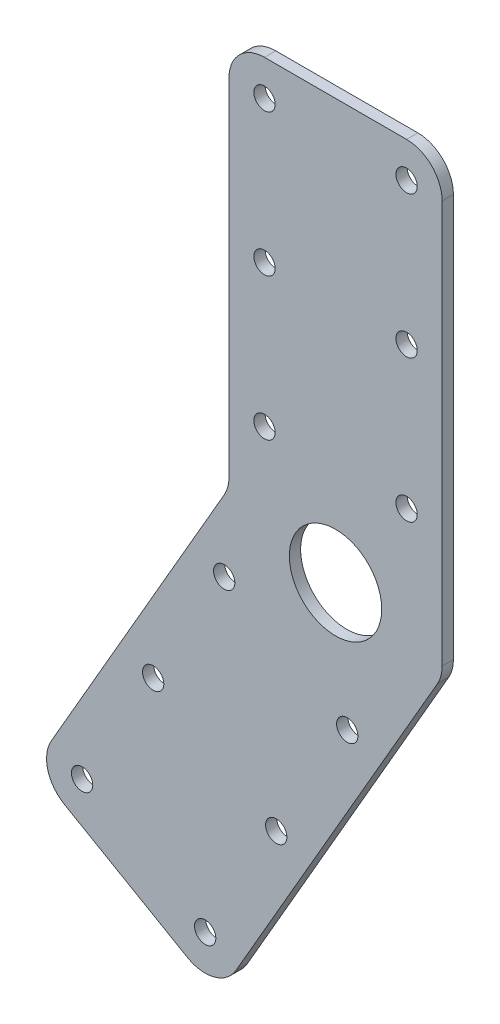
SolidWorks part; units mm, degrees
material "6061 Alloy"
ref_plane "Front Plane" through (0, 0, 0) normal (0, 0, 1) x (1, 0, 0)
ref_plane "Top Plane" through (0, 0, 0) normal (0, 1, 0) x (1, 0, 0)
ref_plane "Right Plane" through (0, 0, 0) normal (1, 0, 0) x (0, 0, -1)
sketch "Sketch1" plane through (0, 0, 0) normal (0, 0, 1) x (1, 0, 0)
  line L0 (0, 0) -> (0, 55)
  line L1 (0, 55) -> (30, 55)
  line L2 (30, 55) -> (30, -8.0385)
  line L3 (30, -8.0385) -> (-1.5192, -62.6314)
  line L4 (-1.5192, -62.6314) -> (-27.5, -47.6314)
  line L5 (-27.5, -47.6314) -> (0, 0)
  line L6 (0, 0) -> (30, -8.0385) construction
  line L7 (5, 55) -> (5, 0) construction
  line L8 (0, 0) -> (5, 0) construction
  line L9 (5, 50) -> (5, 55) construction
  line L10 (15, 55) -> (15, -4.0192) construction
  line L11 (-23.1699, -50.1314) -> (4.3301, -2.5) construction
  line L12 (0, 0) -> (4.3301, -2.5) construction
  line L13 (0, 27.5) -> (5, 30) construction
  line L15 (-14.5096, -55.1314) -> (15, -4.0192) construction
  line L16 (15, -4.0192) -> (7.9904, -16.1603) construction
  line L17 (7.9904, -16.1603) -> (16.6506, -21.1603) construction
  circle A0 centre (15, -4.0192) radius 6.5
  circle A1 centre (5, 50) radius 1.5
  circle A2 centre (5, 30) radius 1.5
  circle A3 centre (5, 10) radius 1.5
  circle A4 centre (25, 10) radius 1.5
  circle A5 centre (25, 30) radius 1.5
  circle A6 centre (25, 50) radius 1.5
  circle A7 centre (-20.6699, -45.8013) radius 1.5
  circle A8 centre (-10.6699, -28.4808) radius 1.5
  circle A9 centre (-0.6699, -11.1603) radius 1.5
  circle A10 centre (16.6506, -21.1603) radius 1.5
  circle A11 centre (6.6506, -38.4808) radius 1.5
  circle A12 centre (-3.3494, -55.8013) radius 1.5
  point P26 (-9.2164, -29.3199)
  dimension "D5" = 13
  dimension "D7" = 3
  dimension "D9" = 20
  dimension "D10" = 20
  dimension "D11" = 5
  dimension "D1" = 30
  dimension "D2" = 55
  dimension "D3" = 55
  dimension "D4" = 150
  dimension "D6" = 5
  dimension "D8" = 5
  dimension "D12" = 20
  dimension "D13" = 20
extrude "Boss-Extrude1" add sketch "Sketch1" along normal blind 1.5875
fillet "Fillet1" radius 5 6 edges at (30, -8.0385, 0.7937) (0, 0, 0.7937) (-1.5192, -62.6314, 0.7937) (-27.5, -47.6314, 0.7937) (0, 55, 0.7937) (30, 55, 0.7937)
